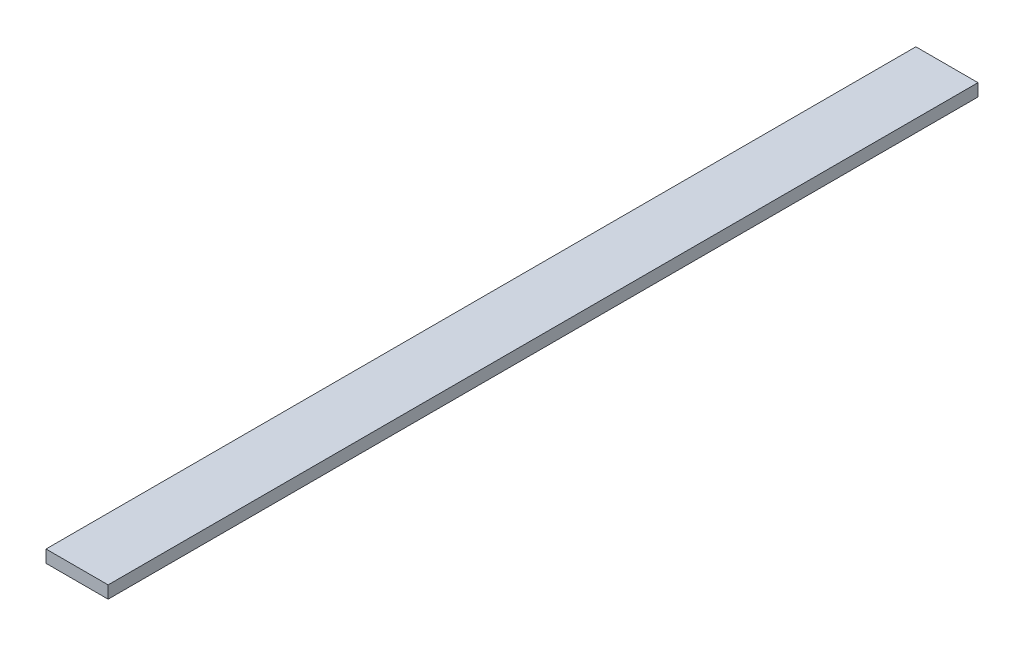
SolidWorks part; units mm, degrees
material "PP homopolimer"
ref_plane "Płaszczyzna przednia" through (0, 0, 0) normal (0, 0, 1) x (1, 0, 0)
ref_plane "Płaszczyzna górna" through (0, 0, 0) normal (0, 1, 0) x (1, 0, 0)
ref_plane "Płaszczyzna prawa" through (0, 0, 0) normal (1, 0, 0) x (0, 0, -1)
sketch "Szkic1" plane through (0, 0, 0) normal (0, 1, 0) x (1, 0, 0)
  line L1 (-12.5, -175) -> (12.5, -175)
  line L2 (-12.5, -175) -> (-12.5, 175)
  line L3 (-12.5, 175) -> (12.5, 175)
  line L4 (12.5, -175) -> (12.5, 175)
  line L5 (0, 175) -> (0, -175) construction
  line L6 (-12.5, 0) -> (12.5, 0) construction
  point P0 (0, 0)
  dimension "D1" = 25
  dimension "D2" = 350
extrude "Dodanie-wyciągnięcie1" add sketch "Szkic1" along normal blind 5
